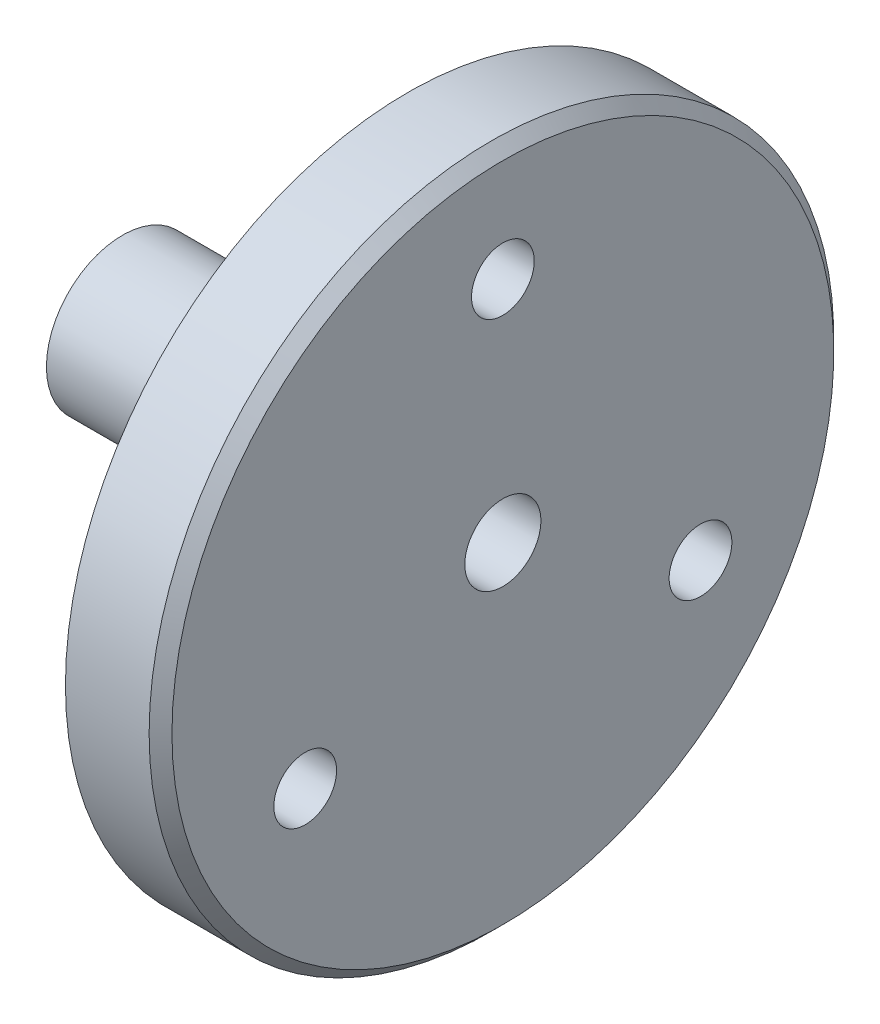
SolidWorks part; units mm, degrees
ref_plane "Plan de face" through (0, 0, 0) normal (0, 0, 1) x (1, 0, 0)
ref_plane "Plan de dessus" through (0, 0, 0) normal (0, 1, 0) x (1, 0, 0)
ref_plane "Plan de droite" through (0, 0, 0) normal (1, 0, 0) x (0, 0, -1)
sketch "Esquisse1" plane through (0, 0, 0) normal (0, 0, 1) x (1, 0, 0)
  line L0 (0, 0) -> (10.7365, 0) construction
  line L1 (0, 2) -> (20, 2)
  line L2 (20, 2) -> (20, 18)
  line L3 (20, 18) -> (15, 18)
  line L4 (15, 18) -> (15, 7.5)
  line L5 (9, 4) -> (0, 4)
  line L6 (0, 4) -> (0, 2)
  line L7 (9, 4) -> (9, 7.5)
  line L8 (9, 7.5) -> (15, 7.5)
  dimension "D1" = 4
  dimension "D2" = 20
  dimension "D3" = 36
  dimension "D4" = 5
  dimension "D5" = 15
  dimension "D6" = 6
  dimension "D7" = 8
revolve "Révolution1" add sketch "Esquisse1" angle 360 about L0
sketch "Esquisse2" plane through (0, 0, 0) normal (0, 0, 1) x (1, 0, 0)
  line L0 (20, -18) -> (20, 18) construction
  circle A0 centre (12, 0) radius 1.25
  point P2 (0, 0)
  dimension "D1" = 2.5
  dimension "D2" = 8
extrude "Enlèv. mat.-Extru.1" cut sketch "Esquisse2" against normal through all
hole_wizard "Trou taraudé M41" positions "Esquisse4" profile "Esquisse5" tap size "M4" standard "ISO" end condition through all
sketch "Esquisse4" plane through (20, 0, 0) normal (1, 0, 0) x (0, 0, -1)
  line L0 (0, 12) -> (0, 0) construction
  point P0 (0, 12)
  dimension "D1" = 12
sketch "Esquisse5" plane through (20, 12, 0) normal (0, 1, 0) x (0, 0, -1)
  line L0 (0, 0) -> (0, 20)
  line L1 (0, 20) -> (1.65, 20)
  line L2 (1.65, 20) -> (1.65, 0)
  line L5 (1.65, 0) -> (0, 0)
  line L11 (0, -6.35) -> (0, 107.95) construction
  dimension "Diamètre du trou pour taraudage jusqu'au prochain" = 3.3
  dimension "Profondeur du trou pour taraudage jusqu'au prochain" = 20
cosmetic thread "Filetage de perçage1" parameters "D2"=4
pattern_circular "Répétition circulaire1" count 3 over 360 about axis through (0, 0, 0) along (1, 0, 0) of "Trou taraudé M41"
cosmetic thread "Filetage de perçage2" parameters "D2"=4
cosmetic thread "Filetage de perçage3" parameters "D2"=4
chamfer "Chanfrein1" distance 0.6 angle 45 1 edges at (20, 0, 18)
